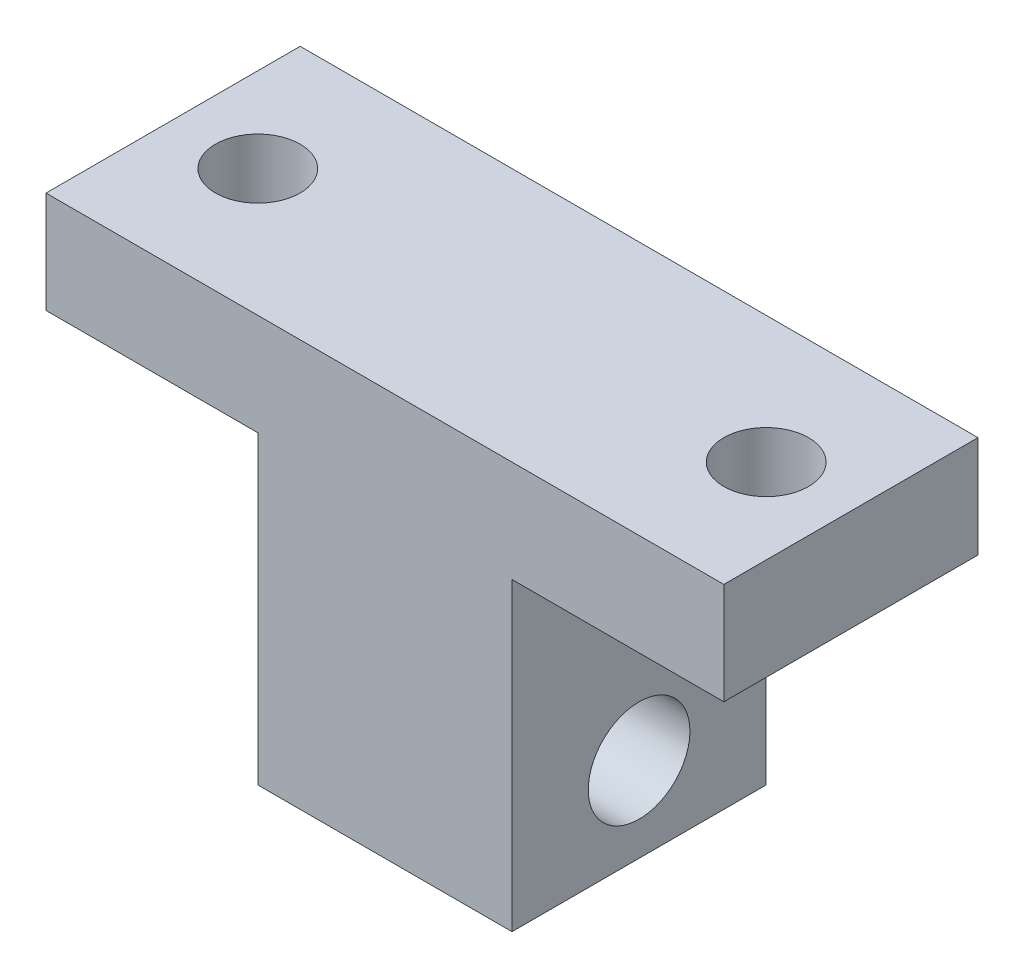
SolidWorks part; units mm, degrees
ref_plane "Front" through (0, 0, 0) normal (0, 0, 1) x (1, 0, 0)
ref_plane "Top" through (0, 0, 0) normal (0, 1, 0) x (1, 0, 0)
ref_plane "Right" through (0, 0, 0) normal (1, 0, 0) x (0, 0, -1)
sketch "草图1" plane through (0, 0, 0) normal (0, 0, 1) x (1, 0, 0)
  line L0 (-20, 0) -> (20, 0)
  line L1 (20, 0) -> (20, -6)
  line L2 (20, -6) -> (7.5, -6)
  line L3 (7.5, -6) -> (7.5, -24)
  line L4 (7.5, -24) -> (-7.5, -24)
  line L5 (-7.5, -24) -> (-7.5, -6)
  line L6 (-7.5, -6) -> (-20, -6)
  line L7 (-20, -6) -> (-20, 0)
  point P4 (0, 0)
  dimension "D1" = 40
  dimension "D2" = 15
  dimension "D3" = 6
  dimension "D4" = 24
extrude "凸台-拉伸1" add sketch "草图1" along normal blind 15
sketch "草图2" plane through (0, -6, 0) normal (0, -1, 0) x (1, 0, 0)
  line L0 (20, 15) -> (20, 0) construction
  circle A0 centre (15, 7.5) radius 2.5
  point P5 (20, 7.5)
  dimension "D1" = 5
  dimension "D2" = 5
extrude "切除-拉伸1" cut sketch "草图2" against normal through all
mirror "镜向1" about plane through (0, 0, 0) normal (1, 0, 0) of "切除-拉伸1"
sketch "草图3" plane through (7.5, 0, 0) normal (1, 0, 0) x (0, 0, -1)
  line L0 (-15, -24) -> (0, -24) construction
  circle A0 centre (-7.5, -19) radius 3
  point P4 (-7.5, -24)
  dimension "D1" = 6
  dimension "D2" = 5
extrude "切除-拉伸2" cut sketch "草图3" against normal through all
